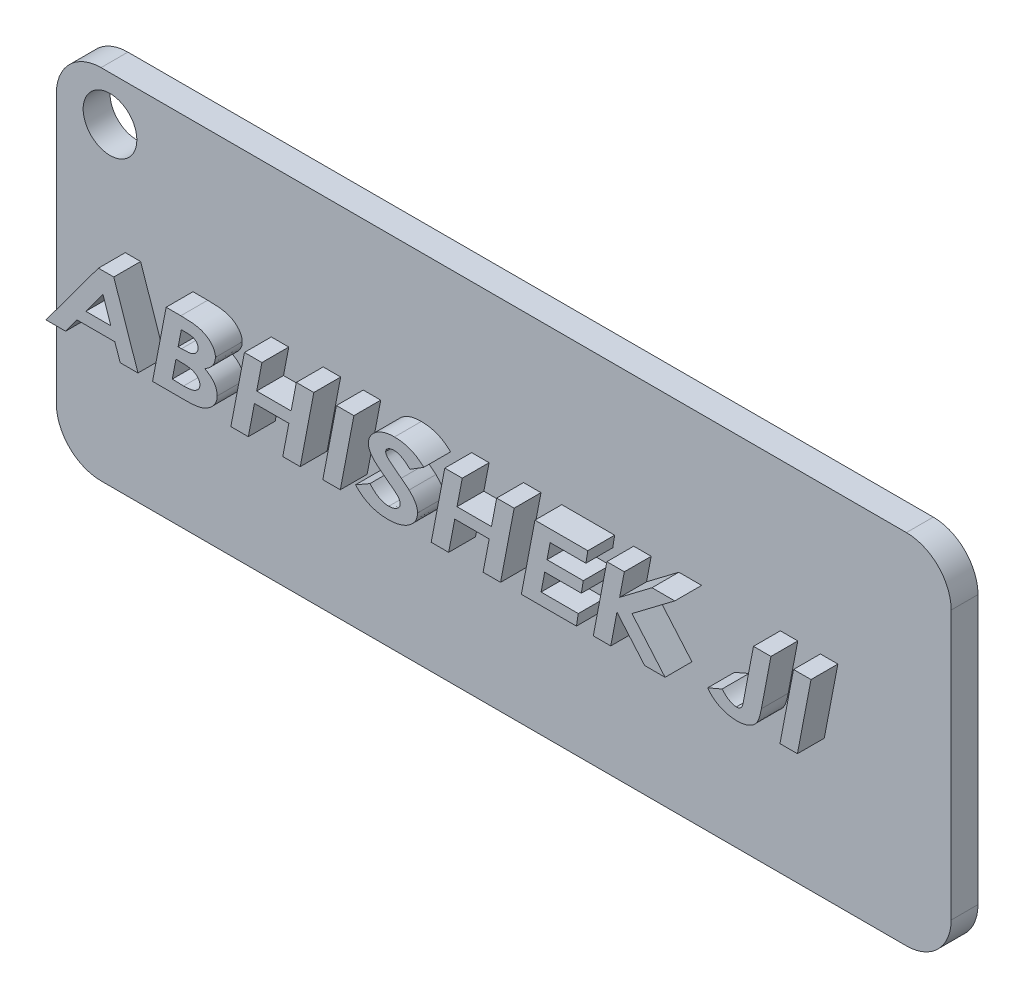
SolidWorks part; units mm, degrees
ref_plane "Front Plane" through (0, 0, 0) normal (0, 0, 1) x (1, 0, 0)
ref_plane "Top Plane" through (0, 0, 0) normal (0, 1, 0) x (1, 0, 0)
ref_plane "Right Plane" through (0, 0, 0) normal (1, 0, 0) x (0, 0, -1)
sketch "Sketch1" plane through (0, 0, 0) normal (0, 0, 1) x (1, 0, 0)
  line L1 (-22.5, -10) -> (22.5, -10)
  line L2 (-25, -7.5) -> (-25, 7.5)
  line L3 (-22.5, 10) -> (22.5, 10)
  line L4 (25, -7.5) -> (25, 7.5)
  line L5 (-25, -10) -> (25, 10) construction
  line L6 (-25, 10) -> (25, -10) construction
  arc A0 (-22.5, -10) -> (-25, -7.5) centre (-22.5, -7.5) cw
  arc A1 (25, -7.5) -> (22.5, -10) centre (22.5, -7.5) cw
  arc A2 (25, 7.5) -> (22.5, 10) centre (22.5, 7.5) ccw
  arc A3 (-22.5, 10) -> (-25, 7.5) centre (-22.5, 7.5) ccw
  point P0 (0, 0)
  dimension "D3" = 2.5
  dimension "D1" = 50
  dimension "D2" = 20
extrude "Boss-Extrude1" add sketch "Sketch1" along normal blind 1.5
sketch "Sketch2" plane through (0, 0, 1.5) normal (0, 0, 1) x (1, 0, 0)
  text T0 "ABHISHEK JI" font "Century Gothic" height in points 15
extrude "Boss-Extrude2" add sketch "Sketch2" along normal blind 1.5
sketch "Sketch3" plane through (0, 0, 1.5) normal (0, 0, 1) x (1, 0, 0)
  line L0 (-25, 7.5) -> (-25, -7.5) construction
  line L1 (22.5, 10) -> (-22.5, 10) construction
  circle A0 centre (-22, 7.5) radius 1.5
  dimension "D1" = 3
  dimension "D2" = 2.5
extrude "Cut-Extrude1" cut sketch "Sketch3" against normal blind 1.5
